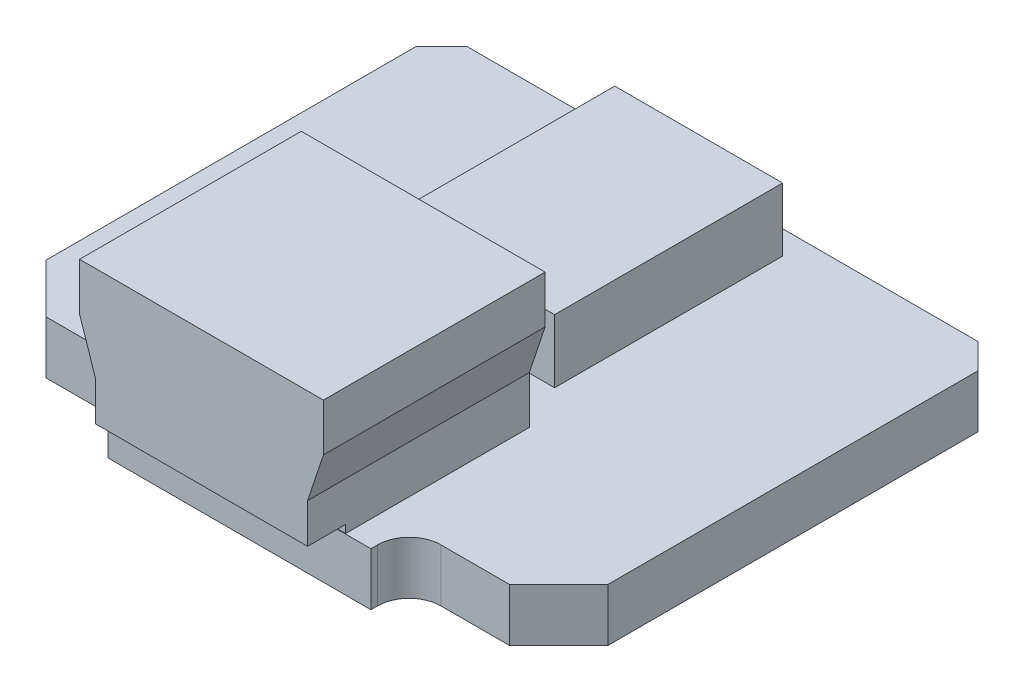
SolidWorks part; units mm, degrees
ref_plane "Front Plane" through (0, 0, 0) normal (0, 0, 1) x (1, 0, 0)
ref_plane "Top Plane" through (0, 0, 0) normal (0, 1, 0) x (1, 0, 0)
ref_plane "Right Plane" through (0, 0, 0) normal (1, 0, 0) x (0, 0, -1)
sketch "PCB Sketch" plane through (0, 0, 0) normal (0, 1, 0) x (1, 0, 0)
  line L0 (-8.07, 7.625) -> (8.07, 7.625)
  line L1 (8.87, 6.825) -> (8.87, -4.865)
  line L2 (7.32, -6.415) -> (5.15, -6.415)
  line L3 (4.15, -7.415) -> (4.15, -7.625)
  line L4 (4.15, -7.625) -> (-4.15, -7.625)
  line L5 (-4.15, -7.625) -> (-4.15, -7.415)
  line L6 (-5.15, -6.415) -> (-7.32, -6.415)
  line L7 (-8.87, -4.865) -> (-8.87, 6.825)
  line L8 (-8.87, 6.825) -> (-8.07, 7.625)
  line L9 (8.07, 7.625) -> (8.87, 6.825)
  line L10 (-7.32, -6.415) -> (-8.87, -4.865)
  line L11 (8.87, -4.865) -> (7.32, -6.415)
  line L12 (0, -7.625) -> (0, 7.625) construction
  arc A0 (-4.15, -7.415) -> (-5.15, -6.415) centre (-5.15, -7.415) ccw
  arc A1 (5.15, -6.415) -> (4.15, -7.415) centre (5.15, -7.415) ccw
  point P0 (-8.87, 7.625)
  point P1 (8.87, 7.625)
  point P3 (8.87, -6.415)
  point P8 (-8.87, -6.415)
  dimension "D5" = 1
  dimension "D6" = 1
  dimension "D1" = 17.74
  dimension "D2" = 14.04
  dimension "D3" = 8.3
  dimension "D4" = 15.25
extrude "PCB" add sketch "PCB Sketch" along normal blind 1.67
sketch "Sketch2" plane through (0, 1.67, 0) normal (0, 1, 0) x (1, 0, 0)
  line L0 (-2.65, 6.875) -> (2.65, 6.875)
  line L1 (2.65, 6.875) -> (2.65, -0.325)
  line L2 (2.65, -0.325) -> (-2.65, -0.325)
  line L3 (-2.65, -0.325) -> (-2.65, 6.875)
  line L6 (8.07, 7.625) -> (-8.07, 7.625) construction
  line L7 (-4.15, -7.625) -> (4.15, -7.625) construction
  point P7 (0, 6.875)
  point P8 (0, 7.625)
  dimension "D1" = 5.3
  dimension "D2" = 7.2
  dimension "D3" = 0
  dimension "D4" = 7.3
extrude "PIC18" add sketch "Sketch2" along normal blind 2
sketch "Sketch3" plane through (0, 0, 0) normal (0, -1, 0) x (1, 0, 0)
  line L0 (-6.04, 1.585) -> (-6.04, -4.795) construction
  line L1 (-3.81, 1.585) -> (-3.81, -4.795)
  line L2 (-8.27, 1.585) -> (-8.27, -4.795)
  line L3 (-8.87, -6.825) -> (-8.87, 4.865) construction
  line L4 (8.07, -7.625) -> (-8.07, -7.625) construction
  arc A0 (-3.81, 1.585) -> (-8.27, 1.585) centre (-6.04, 1.585) ccw
  arc A1 (-8.27, -4.795) -> (-3.81, -4.795) centre (-6.04, -4.795) ccw
  point P2 (-6.04, -1.605)
  point P9 (-6.04, -7.025)
  dimension "D1" = 0.6
  dimension "D2" = 0.6
extrude "Crystal" add sketch "Sketch3" along normal blind 0.72
sketch "Sketch5" plane through (0, -0.72, 0) normal (0, -1, 0) x (1, 0, 0)
  line L0 (-6.04, 1.585) -> (-6.04, -4.715) construction
  line L1 (-4.255, 1.585) -> (-4.255, -4.715)
  line L2 (-7.825, 1.585) -> (-7.825, -4.715)
  arc A0 (-4.255, 1.585) -> (-7.825, 1.585) centre (-6.04, 1.585) ccw
  arc A1 (-7.825, -4.715) -> (-4.255, -4.715) centre (-6.04, -4.715) ccw
  arc A2 (-8.27, -4.795) -> (-3.81, -4.795) centre (-6.04, -4.795) ccw construction
  point P2 (-6.04, -1.565)
  point P7 (-6.04, -6.5)
  point P8 (-6.04, -7.025)
  dimension "D1" = 0
  dimension "D2" = 0
extrude "Boss-Extrude4" add sketch "Sketch5" along normal blind 2.5
sketch3d "3DSketch1"
  line L0 (-3.8496, 6.1844, 1.825) -> (3.8504, 6.1844, 1.825)
  line L1 (3.8504, 6.1844, 1.825) -> (3.8504, 4.6844, 1.825)
  line L2 (3.8504, 4.6844, 1.825) -> (3.3504, 3.1844, 1.825)
  line L3 (3.3504, 3.1844, 1.825) -> (3.3504, 1.6844, 1.825)
  line L4 (3.3504, 1.6844, 1.825) -> (-3.3496, 1.6844, 1.825)
  line L6 (-3.3496, 3.1844, 1.825) -> (-3.3496, 1.6844, 1.825)
  line L7 (-3.8496, 4.6844, 1.825) -> (-3.3496, 3.1844, 1.825)
  line L8 (-3.8496, 6.1844, 1.825) -> (-3.8496, 4.6844, 1.825)
  dimension "D2" = 0.0144
  dimension "D5" = 1.5
  dimension "D6" = 1.5
  dimension "D1" = 1.5811
extrude "USB Connector" add sketch "3DSketch1" along direction (0, 0, -1) on the side of the normal blind 7 separate body
sketch "Sketch6" plane through (0, 0, 8.825) normal (0, 0, 1) x (1, 0, 0)
  line L0 (3.3504, 3.1844) -> (3.3504, 1.6844) construction
  line L1 (-3.3496, 1.6844) -> (3.3504, 1.6844)
  line L2 (-3.3496, 1.6844) -> (-3.3496, 1.9344)
  line L3 (-3.3496, 1.9344) -> (3.3504, 1.9344)
  line L4 (3.3504, 1.6844) -> (3.3504, 1.9344)
  dimension "D1" = 0.25
extrude "Cut-Extrude1" cut sketch "Sketch6" against normal up to surface (1.2 mm away) up to face at (0, 0.835, 7.625)
